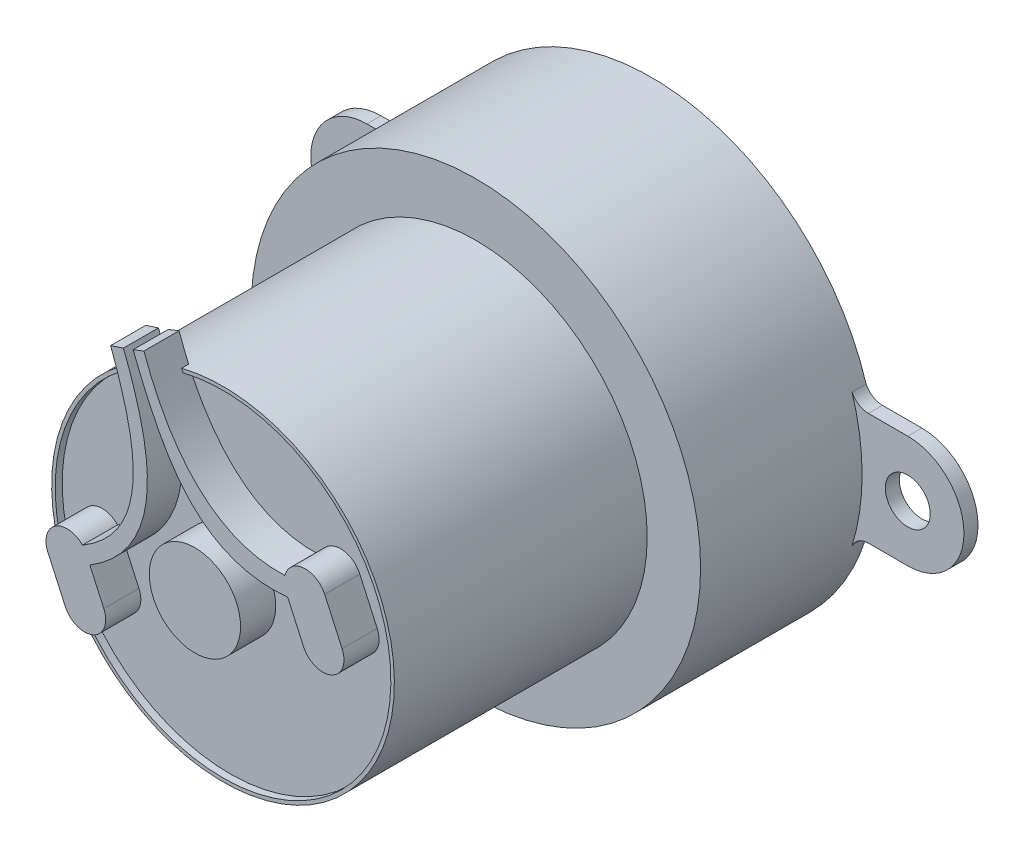
SolidWorks part; units mm, degrees
ref_plane "Alzado" through (0, 0, 0) normal (0, 0, 1) x (1, 0, 0)
ref_plane "Planta" through (0, 0, 0) normal (0, 1, 0) x (1, 0, 0)
ref_plane "Vista lateral" through (0, 0, 0) normal (1, 0, 0) x (0, 0, -1)
sketch "Croquis1" plane through (0, 0, 0) normal (0, 0, 1) x (1, 0, 0)
  line L2 (-19.25, 4) -> (-16.45, 4)
  line L3 (-19.25, -4) -> (-16.45, -4)
  line L5 (19.25, 4) -> (16.45, 4)
  line L6 (19.25, -4) -> (16.45, -4)
  arc A0 (-15.2847, 4.7306) -> (15.2847, 4.7306) centre (0, 0) cw
  circle A1 centre (-19.25, 0) radius 1.6
  circle A2 centre (19.25, 0) radius 1.6
  arc A3 (-19.25, 4) -> (-19.25, -4) centre (-19.25, 0) ccw
  arc A4 (-16.45, 4) -> (-15.2847, 4.7306) centre (-16.45, 5.2947) ccw
  arc A5 (19.25, 4) -> (19.25, -4) centre (19.25, 0) cw
  arc A6 (-16.45, -4) -> (-15.2847, -4.7306) centre (-16.45, -5.2947) cw
  arc A7 (16.45, 4) -> (15.2847, 4.7306) centre (16.45, 5.2947) cw
  arc A8 (16.45, -4) -> (15.2847, -4.7306) centre (16.45, -5.2947) ccw
  arc A9 (-15.2847, -4.7306) -> (15.2847, -4.7306) centre (0, 0) ccw
extrude "Saliente-Extruir1" add sketch "Croquis1" along normal blind 1 contours A6 A9 A8 L6 A5 L5 A7 A0 A4 L2 A3 L3 A1 A2
sketch "Croquis2" plane through (0, 0, 1) normal (0, 0, 1) x (1, 0, 0)
  circle A0 centre (0, 0) radius 16
extrude "Saliente-Extruir2" add sketch "Croquis2" along normal blind 11.5
sketch "Croquis3" plane through (0, 0, 12.5) normal (0, 0, 1) x (1, 0, 0)
  circle A0 centre (0, 0) radius 12.2
extrude "Saliente-Extruir3" add sketch "Croquis3" along normal blind 18
sketch "Croquis4" plane through (0, 0, 30.5) normal (0, 0, 1) x (1, 0, 0)
  circle A0 centre (0, 0) radius 11.95
extrude "Cortar-Extruir1" cut sketch "Croquis4" against normal blind 0.5
sketch "Croquis5" plane through (0, 0, 30) normal (0, 0, 1) x (1, 0, 0)
  circle A0 centre (0, 0) radius 3.25
extrude "Saliente-Extruir4" add sketch "Croquis5" along normal blind 2.5
sketch "Croquis6" plane through (0, 0, 30) normal (0, 0, 1) x (1, 0, 0)
  line L0 (0, 0) -> (0, 3)
  line L2 (0, 0) -> (0, -3)
  line L11 (-7.8597, -4.3736) -> (-9.0982, -1.6412) construction
  line L12 (-9.2321, -4.9957) -> (-10.4707, -2.2633)
  line L13 (9.1046, 1.6338) -> (7.866, 4.3662) construction
  line L14 (7.7321, 1.0117) -> (6.4936, 3.7441)
  line L15 (10.477, 2.2559) -> (9.2384, 4.9883)
  line L16 (-6.4872, -3.7515) -> (-7.7258, -1.0191)
  arc A5 (7.7321, 1.0117) -> (10.477, 2.2559) centre (9.1046, 1.6338) ccw
  arc A6 (9.2384, 4.9883) -> (6.4936, 3.7441) centre (7.866, 4.3662) ccw
  arc A7 (-9.2321, -4.9957) -> (-6.4872, -3.7515) centre (-7.8597, -4.3736) ccw
  arc A8 (-7.7258, -1.0191) -> (-10.4707, -2.2633) centre (-9.0982, -1.6412) ccw
  point P1 (0, 0)
  point P25 (8.4853, 3)
  point P33 (-8.479, -3.0074)
extrude "Saliente-Extruir6" add sketch "Croquis6" along normal blind 2.5 contours L15 A6 L14 A5 | L16 A8 L12 A7
sketch "Croquis7" plane through (0, 0, 30) normal (0, 0, 1) x (1, 0, 0)
  line L0 (0, 0) -> (-3.9433, 11.2806)
  line L1 (11.4925, 4.0942) -> (-11.4925, -4.0942)
  line L2 (-9.191, -1.2011) -> (-8.7496, -2.2322)
  line L3 (-5.9993, 12.7081) -> (-5.0936, 13.0048)
  line L4 (-4.403, 13.2503) -> (-3.6296, 13.5582)
  line L5 (6.9385, 4.7735) -> (7.3896, 3.6071)
  circle A0 centre (0, 0) radius 12.2 construction
  circle A1 centre (0, 0) radius 11.95 construction
  spline S0 degree 3 poles (-8.7496, -2.2322) (-1.4984, 1.1235) (-3.0425, 7.7943) (-5.0936, 13.0048) knots 0 0 0 0 1 1 1 1
  spline S1 degree 3 poles (-9.191, -1.2011) (-2.4487, 1.7478) (-4.2591, 7.9249) (-5.9993, 12.7081) knots 0 0 0 0 1 1 1 1
  spline S2 degree 3 poles (7.3896, 3.6071) (0.0737, 2.3955) (-2.3925, 8.2872) (-4.403, 13.2503) knots 0 0 0 0 1 1 1 1
  spline S3 degree 3 poles (6.9385, 4.7735) (1.1089, 4.2005) (-2.022, 9.0323) (-3.6296, 13.5582) knots 0 0 0 0 1 1 1 1
  arc M1 (-10.4707, -2.2633) -> (-7.7258, -1.0191) centre (-9.0982, -1.6412) cw
  line M2 (-7.7258, -1.0191) -> (-6.4872, -3.7515)
  arc M5 (6.4936, 3.7441) -> (9.2384, 4.9883) centre (7.866, 4.3662) cw
  line M8 (7.7321, 1.0117) -> (6.4936, 3.7441)
  circle M10 centre (0, 0) radius 11.95
extrude "Saliente-Extruir7" add sketch "Croquis7" along normal blind 2.5 contours S1 S0 M1 M2 M10 | S1 S0 L3 M10 | S3 L4 S2 M10 | S3 S2 M5 M10 M8
sketch "Croquis8" plane through (0, 0, 0) normal (0, 0, -1) x (-1, 0, 0)
  text T0 "KINGLY\r\nMOTOR" font "Arial Narrow" height in points 9
extrude "Cortar-Extruir2" cut sketch "Croquis8" against normal blind 0.5
sketch "Croquis9" plane through (0, 0, 0) normal (0, 0, -1) x (-1, 0, 0)
  circle A0 centre (0, -8) radius 4.85
extrude "Saliente-Extruir8" add sketch "Croquis9" along normal blind 2
sketch "Croquis11" plane through (0, 0, -2) normal (0, 0, -1) x (-1, 0, 0)
  circle A0 centre (0, -8) radius 4
extrude "Saliente-Extruir9" add sketch "Croquis11" along normal blind 0.2
sketch "Croquis12" plane through (0, 0, -2.2) normal (0, 0, -1) x (-1, 0, 0)
  circle A0 centre (0, -8) radius 2.5
extrude "Saliente-Extruir10" add sketch "Croquis12" along normal blind 1.2
sketch "Croquis13" plane through (0, 0, -3.4) normal (0, 0, -1) x (-1, 0, 0)
  line L2 (0, -9.5) -> (-2, -9.5)
  line L3 (0, -9.5) -> (2, -9.5)
  line L4 (0, -6.5) -> (2, -6.5)
  line L5 (0, -6.5) -> (-2, -6.5)
  circle A0 centre (0, -8) radius 2.5 construction
  arc A1 (2, -9.5) -> (2, -6.5) centre (0, -8) ccw
  arc A2 (-2, -6.5) -> (-2, -9.5) centre (0, -8) ccw
extrude "Saliente-Extruir11" add sketch "Croquis13" along normal blind 6.7
sketch "Croquis14" plane through (0, 0, 0) normal (0, 0, -1) x (-1, 0, 0)
  circle A0 centre (9, -9) radius 1.6
  circle A1 centre (-9, 9) radius 1.6
extrude "Saliente-Extruir12" add sketch "Croquis14" along normal blind 0.2
sketch "Croquis15" plane through (0, 0, -0.2) normal (0, 0, -1) x (-1, 0, 0)
  text T0 "*"
  point P1 (6.4035, -11.4673)
  point P2 (0, 0)
  point P3 (7.8886, -11.9308)
  point P4 (7.66, -11.7528)
  point P5 (7.8767, -11.7318)
  point P6 (7.9933, -11.6887)
extrude "Cortar-Extruir3" cut sketch "Croquis15" against normal blind 0.2
sketch "Croquis16" plane through (0, 0, -0.2) normal (0, 0, -1) x (-1, 0, 0)
  text T0 "*"
  point P1 (-11.2316, 5.8037)
  point P2 (-10.6962, 5.8609)
  point P3 (-10.508, 6.1337)
  point P4 (-10.1151, 6.3186)
  point P5 (-9.9863, 6.3401)
  point P6 (-9.9694, 6.2919)
  point P7 (-9.993, 6.2149)
  point P8 (-9.9945, 6.2786)
extrude "Cortar-Extruir4" cut sketch "Croquis16" against normal blind 0.2
